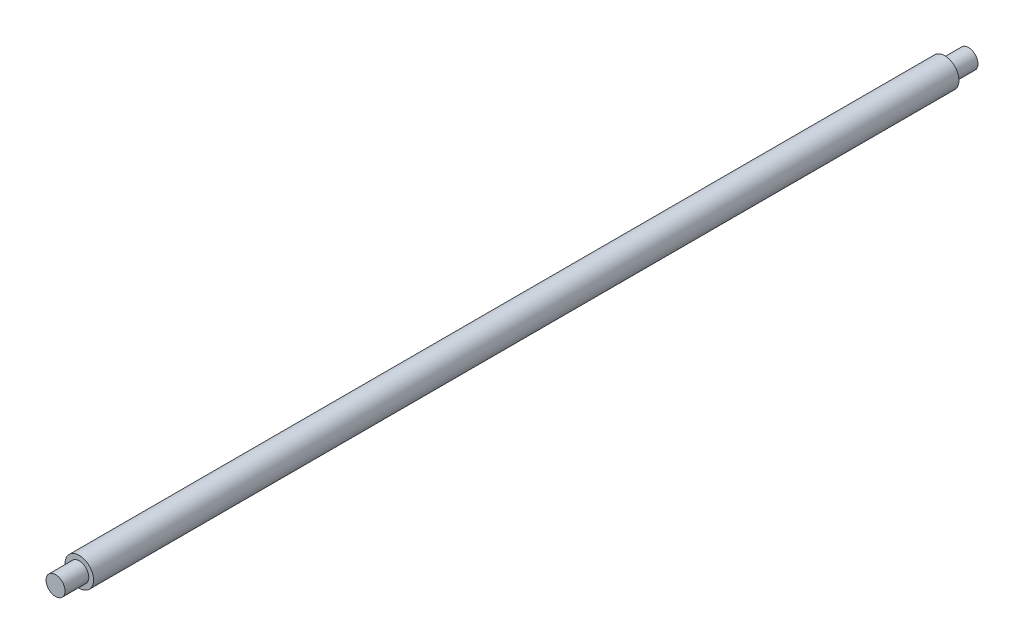
SolidWorks part; units mm, degrees
ref_plane "Front Plane" through (0, 0, 0) normal (0, 0, 1) x (1, 0, 0)
ref_plane "Top Plane" through (0, 0, 0) normal (0, 1, 0) x (1, 0, 0)
ref_plane "Right Plane" through (0, 0, 0) normal (1, 0, 0) x (0, 0, -1)
sketch "Sketch1" plane through (0, 0, 0) normal (0, 0, 1) x (1, 0, 0)
  circle A0 centre (0, 0) radius 6.35 construction
  circle A1 centre (0, 0) radius 6.35
  circle A2 centre (0, 0) radius 9.525
  dimension "D1" = 19.05
sketch "Sketch2" plane through (0, 0, 0) normal (0, 0, 1) x (1, 0, 0)
  circle A0 centre (0, 0) radius 9.525
extrude "Boss-Extrude3" add sketch "Sketch1" against normal up to surface (12.7 mm away) and the other way up to surface (596.9 mm away) contours A1
ref_plane "Plane1" through (0, 0, 3.175) normal (0, 0, 1) x (1, 0, 0)
ref_plane "Plane2" through (0, 0, 581.025) normal (0, 0, -1) x (-1, 0, 0)
sketch "Sketch3" plane through (0, 0, 0) normal (0, 0, 1) x (1, 0, 0)
  circle A0 centre (0, 0) radius 9.525
  dimension "D1" = 19.05
extrude "Boss-Extrude4" add sketch "Sketch3" along normal up to surface (577.85 mm away) from surface at 3.175 up to plane "Plane2" starting at plane "Plane1"
